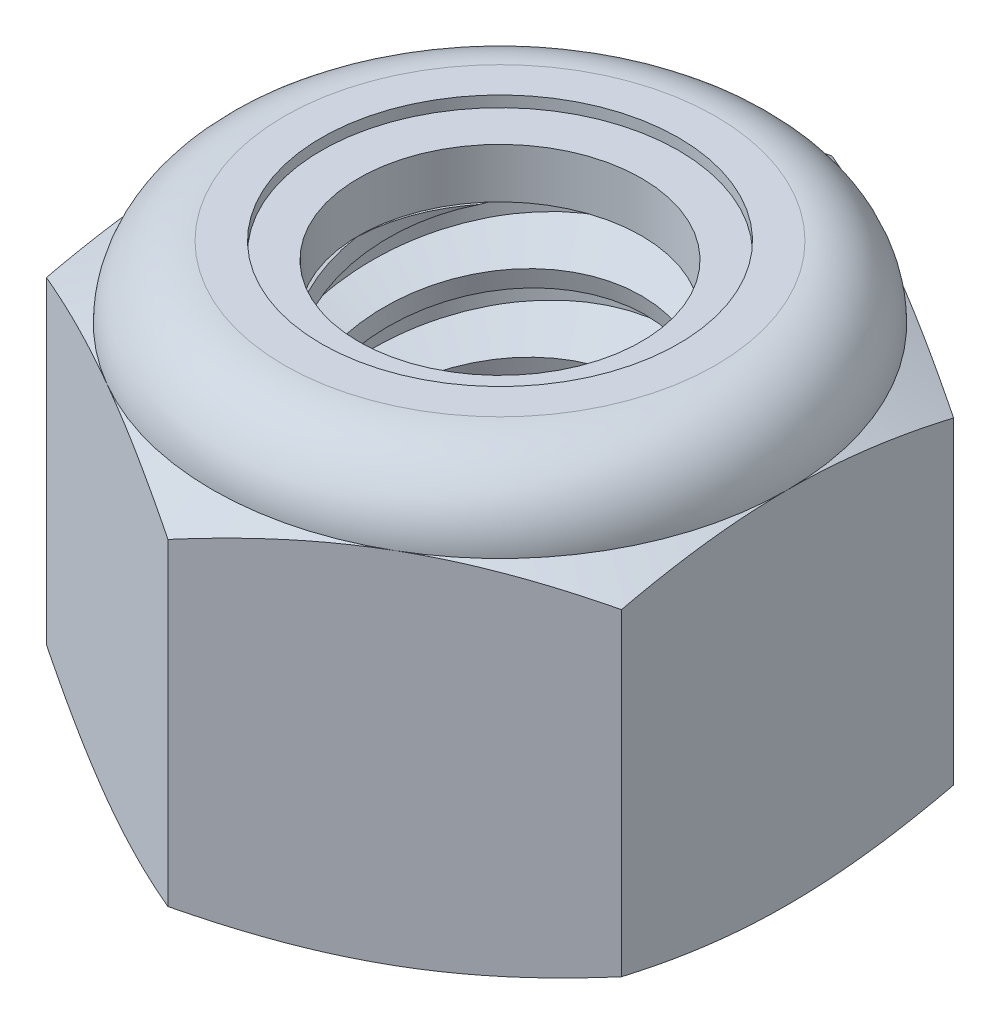
SolidWorks part; units mm, degrees
ref_plane "Front" through (0, 0, 0) normal (0, 0, 1) x (1, 0, 0)
ref_plane "Top" through (0, 0, 0) normal (0, 1, 0) x (1, 0, 0)
ref_plane "Right" through (0, 0, 0) normal (1, 0, 0) x (0, 0, -1)
sketch "Sketch1" plane through (0, 0, 0) normal (0, 1, 0) x (1, 0, 0)
  line L1 (0, 4.5827) -> (-3.9688, 2.2914)
  line L2 (-3.9688, 2.2914) -> (-3.9688, -2.2914)
  line L3 (-3.9688, -2.2914) -> (0, -4.5827)
  line L4 (0, -4.5827) -> (3.9687, -2.2914)
  line L5 (3.9687, -2.2914) -> (3.9687, 2.2914)
  line L6 (3.9687, 2.2914) -> (0, 4.5827)
  circle A0 centre (0, 0) radius 3.9688 construction
  dimension "Hex Flats" = 7.9375
extrude "Extrude1" add sketch "Sketch1" along normal blind 5.9531
sketch "Sketch2" plane through (0, 0, 0) normal (1, 0, 0) x (0, 0, -1)
  line L0 (-2.413, 0) -> (-2.413, 5.9531) construction
  line L1 (0, 0) -> (2.413, 0)
  line L2 (0, 0) -> (0, 5.9531)
  line L3 (0, 5.9531) -> (2.413, 5.9531)
  line L4 (2.413, 0) -> (2.413, 5.9531)
  line L5 (-2.2914, 5.9531) -> (2.2914, 5.9531) construction
  line L7 (0, -2.413) -> (0, 0) construction
  dimension "Thread Dia" = 4.826
revolve "Revolve1" add sketch "Sketch2" angle 360 about L7
sketch "Sketch3" plane through (0, 0, 0) normal (1, 0, 0) x (0, 0, -1)
  line L0 (2.413, 5.9531) -> (-2.413, 5.9531) construction
  line L1 (-2.413, 5.9531) -> (-2.413, 4.8948) construction
  line L2 (-2.413, 4.8948) -> (2.413, 5.9531) construction
  line L3 (2.413, 5.9531) -> (2.4413, 5.8239) construction
  line L4 (2.4413, 5.8239) -> (2.6397, 4.9194)
  line L5 (2.6397, 4.9194) -> (2.0093, 5.1197)
  line L6 (2.0093, 5.1197) -> (1.9526, 5.3781)
  line L7 (1.9526, 5.3781) -> (2.4413, 5.8239)
  line L8 (1.981, 5.2489) -> (2.5405, 5.3716) construction
  line L9 (2.413, 5.9531) -> (2.413, 5.3437) construction
  line L10 (2.413, 5.3437) -> (-2.413, 4.2853) construction
  line L11 (-2.413, 4.2853) -> (-2.413, 4.8948) construction
  line L12 (-0.2497, 5.9531) -> (0.2497, 3.6759) construction
  line L13 (-2.413, 0) -> (-2.413, 5.9531) construction
  line L14 (0, 5.9531) -> (2.413, 5.9531) construction
  line L15 (2.413, 0) -> (2.413, 5.9531) construction
  point P13 (0, 4.8145)
  dimension "D1" = 0.1323
  dimension "D2" = 0.2646
  dimension "Thread Pitch" = 1.0583
  dimension "D4" = 60
  dimension "D5" = 1.0583
revolve "Cut-Revolve1" cut sketch "Sketch3" angle 360 about L12
pattern_linear "LPattern1" count 6 spacing 1.0583 along (0, -1, 0) count 2 spacing 1.0583 along (0, 1, 0) of "Cut-Revolve1"
sketch "Sketch4" plane through (0, 0, 0) normal (1, 0, 0) x (0, 0, -1)
  line L0 (0, 5.9531) -> (2.413, 5.9531)
  line L1 (2.413, 5.9531) -> (1.9526, 5.7385)
  line L2 (1.9526, 5.7385) -> (1.9526, 0.2147)
  line L3 (1.9526, 0.2147) -> (2.413, 0)
  line L4 (2.413, 0) -> (0, 0)
  line L5 (0, 0) -> (0, 5.9531)
  line L6 (2.413, 0) -> (2.413, 5.9531) construction
  line L7 (0, 5.9531) -> (2.413, 5.9531) construction
  line L8 (0, 0) -> (2.413, 0) construction
  line L9 (0, 0) -> (0, 5.9531) construction
  line L10 (0, 5.9531) -> (0, 6.4611) construction
  dimension "D1" = 25
revolve "Cut-Revolve2" cut sketch "Sketch4" angle 360 about L10
combine bodies "Combine1" operation type subtract main body 112 bodies to subtract 111
sketch "Sketch5" plane through (0, 0, 0) normal (1, 0, 0) x (0, 0, -1)
  line L0 (0, 0) -> (3.9688, 0)
  line L1 (3.9688, 0) -> (4.5827, 0.2863)
  line L2 (4.5827, 0.2863) -> (4.5827, 4.6746)
  line L3 (4.5827, 4.6746) -> (3.9688, 4.9609)
  line L4 (2.9766, 5.9531) -> (2.9766, 7.2231)
  line L5 (2.9766, 7.2231) -> (5.8527, 7.2231)
  line L6 (5.8527, 7.2231) -> (5.8527, -1.27)
  line L7 (5.8527, -1.27) -> (0, -1.27)
  line L8 (0, -1.27) -> (0, 0)
  line L9 (3.9688, 4.9609) -> (3.9688, 0) construction
  line L10 (0, 0) -> (2.413, 0) construction
  line L13 (4.5827, 2.4805) -> (5.8527, 2.4805) construction
  line L14 (4.5827, 5.9531) -> (4.5827, 0) construction
  line L15 (0, 0) -> (0, 7.2231) construction
  line L20 (0, 7.2231) -> (2.9766, 7.2231) construction
  line L22 (0, 5.9531) -> (2.413, 5.9531) construction
  arc A0 (3.9688, 4.9609) -> (2.9766, 5.9531) centre (2.9766, 4.9609) ccw
  dimension "D1" = 25
  dimension "D2" = 1.27
  dimension "D3" = 5.9531
  dimension "D4" = 0.9922
revolve "Cut-Revolve3" cut sketch "Sketch5" angle 360 about L15
sketch "Sketch6" plane through (0, 0, 0) normal (1, 0, 0) x (0, 0, -1)
  line L0 (0, 4.9609) -> (3.8163, 4.9609)
  line L1 (2.9766, 5.8007) -> (2.4646, 5.8007)
  line L2 (0, 7.2231) -> (0, 4.9609)
  line L3 (2.4646, 7.2231) -> (0, 7.2231)
  line L4 (0, 7.2231) -> (2.9766, 7.2231) construction
  line L5 (0, 0) -> (0, 7.2231) construction
  line L6 (0, 7.2231) -> (0, 44.323) construction
  line L7 (2.4646, 5.8007) -> (2.4646, 7.2231)
  line L8 (2.9766, 5.9531) -> (2.9766, 5.8007) construction
  line L9 (2.4646, 5.8007) -> (1.9526, 5.8007) construction
  line L10 (1.9526, 5.8007) -> (1.9526, 5.7385) construction
  arc A0 (3.8163, 4.9609) -> (2.9766, 5.8007) centre (2.9766, 4.9609) ccw
  arc A1 (3.9688, 4.9609) -> (2.9766, 5.9531) centre (2.9766, 4.9609) ccw construction
  dimension "D1" = 0.1524
revolve "Cut-Revolve4" cut sketch "Sketch6" angle 360 about L6
sketch "Sketch7" plane through (0, 0, 0) normal (1, 0, 0) x (0, 0, -1)
  line L0 (1.9526, 5.0371) -> (3.7363, 5.0371)
  line L1 (2.9766, 5.7245) -> (1.9526, 5.7245)
  line L2 (1.9526, 5.7245) -> (1.9526, 5.0371)
  line L3 (1.9526, 5.0371) -> (0, 5.0371) construction
  line L4 (0, 5.0371) -> (0, 5.7245) construction
  line L5 (0, 5.7245) -> (1.9526, 5.7245) construction
  line L6 (1.9526, 5.0371) -> (1.9526, 4.9609) construction
  line L7 (0, 4.9609) -> (3.8163, 4.9609) construction
  line L8 (2.9766, 5.7245) -> (2.9766, 5.8007) construction
  arc A0 (3.7363, 5.0371) -> (2.9766, 5.7245) centre (2.9766, 4.9609) ccw
  arc A2 (3.8164, 4.9609) -> (2.9766, 5.8007) centre (2.9766, 4.9609) ccw construction
  dimension "D1" = 0.0762
revolve "Revolve2" add sketch "Sketch7" angle 360 about L4
equation "\"D1@Sketch3\"=\"Thread Pitch@Sketch3\"/8"
equation "\"D2@Sketch3\"=\"Thread Pitch@Sketch3\"/4"
equation "\"D5@Sketch3\"=\"Thread Pitch@Sketch3\""
equation "\"D4@LPattern1\"=\"Thread Pitch@Sketch3\""
equation "\"D3@LPattern1\"=\"Thread Pitch@Sketch3\""
equation "\"D1@LPattern1\"=\"Height@Extrude1\"/\"Thread Pitch@Sketch3\""
equation "\"D4@Sketch5\"=\"Height@Extrude1\"/6"
